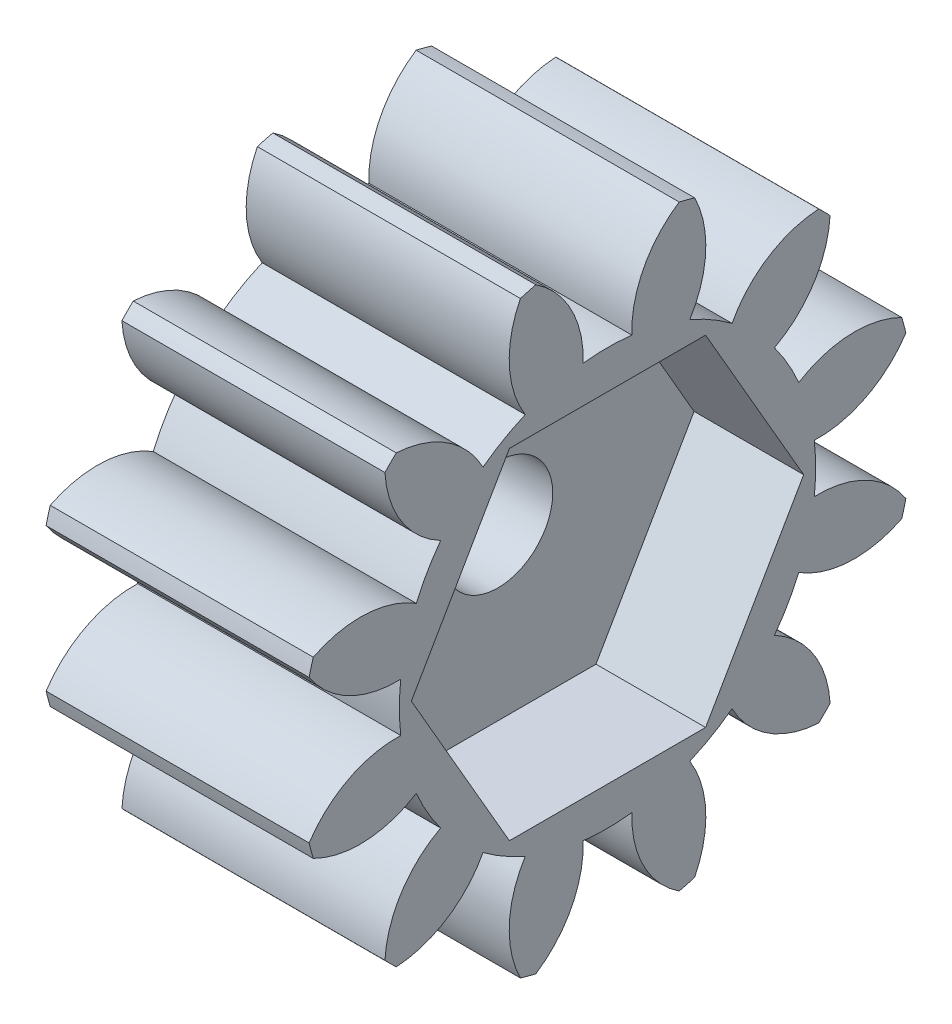
SolidWorks part; units mm, degrees
ref_plane "Plane1" through (0, 0, 0) normal (0, 0, 1) x (1, 0, 0)
ref_plane "Plane2" through (0, 0, 0) normal (0, 1, 0) x (1, 0, 0)
ref_plane "Plane3" through (0, 0, 0) normal (1, 0, 0) x (0, 0, -1)
sketch "HoldingSke" plane through (0, 0, 0) normal (0, 1, 0) x (1, 0, 0)
  line L0 (0, 0) -> (0.4891, -0.104)
  line L1 (-15, 0) -> (100, 0) construction
  line L2 (0, 0) -> (-2.1039, 2.3779)
  line L3 (0, 0) -> (-11.863, 4.5341)
  line L4 (0, 0) -> (8.4473, 1.7955)
  line L5 (0, 0) -> (-46.8476, -17.4728)
  line L6 (0, 0) -> (-9.9476, -6.7116)
  line L7 (-2.1039, 2.3779) -> (8.6586, 51.2059)
  line L8 (-76.2, 54.61) -> (-75.3, 54.61)
  line L9 (-71.009, 38.7566) -> (-53.1078, 45.2721)
  line L10 (-76.2, 71.12) -> (104.1128, 71.12)
  line L11 (0, 0) -> (-12, 0)
  line L12 (-76.2, 101.6) -> (-76.133, 101.6)
  line L13 (24.9733, 27.94) -> (52.9518, 28.4284)
  line L14 (24.9733, 27.94) -> (24.9743, 27.94)
  line L15 (24.9733, 27.94) -> (100.4006, 29.5858)
  line L16 (-63.627, -2) -> (-12.827, -2)
  circle A0 centre (0, 0) radius 2.5
  circle A1 centre (0, 0) radius 9.499
  circle A2 centre (0, 0) radius 37.5
  circle A3 centre (0, 0) radius 2.5
  dimension "MHD" = 18.998
  dimension "Hub_dia" = 75
  dimension "Bore" = 5
  dimension "MBD" = 5
  dimension "Num_teeth" = 12
  dimension "Pitch_radius" = 180.3128
  dimension "Pitch" = 0.5
  dimension "Width" = 12
  dimension "Overall_len" = 50
  dimension "Show_teeth" = 12
  dimension "Thickness" = 12
  dimension "OAL" = 50.0001
  dimension "T_dim" = 0.9
  dimension "Ap" = 20
  dimension "H" = 19.05
  dimension "Backlash" = 0.067
  dimension "Addendum_fac" = 1
  dimension "Dedendum_fac" = 1.25
  dimension "Clearance_fac" = 0.25
  dimension "Dedendum_add" = 0.001
  dimension "Module" = 2
sketch "BasProSke" plane through (0, 0, 0) normal (0, 1, 0) x (1, 0, 0)
  line L0 (-10, 0) -> (60, 0) construction
  line L1 (0, 0) -> (0, 14)
  line L2 (0, 0) -> (12, 0)
  line L3 (12, 0) -> (12, 14)
  line L4 (12, 14) -> (0, 14)
  dimension "Diameter" = 28
  dimension "Thickness" = 12
revolve "Base-Revolve" add sketch "BasProSke" angle 360 about L0
sketch "TooCutSke" plane through (0, 0, 0) normal (1, 0, 0) x (0, 0, -1)
  line L1 (0, 0) -> (0, 107) construction
  line L2 (0, 0) -> (-1.6834, 11.8813) construction
  line L3 (0, 0) -> (-6.1662, 23.0126) construction
  line L4 (-1.6834, 11.8813) -> (-3.0831, 11.5063) construction
  arc A0 (1.1119, 9.4337) -> (-1.1119, 9.4337) centre (0, 0) ccw
  arc A1 (3.2981, 13.6321) -> (-3.2981, 13.6321) centre (0, 0) ccw
  circle A2 centre (0, 0) radius 12 construction
  circle A3 centre (0, 0) radius 11.2763 construction
  arc A4 (-1.1119, 9.4337) -> (-3.2981, 13.6321) centre (-5.9089, 9.6042) ccw
  arc A5 (3.2981, 13.6321) -> (1.1119, 9.4337) centre (5.9089, 9.6042) ccw
  dimension "Root_dia" = 18.998
  dimension "Overcut_dia" = 28.0508
  dimension "Pitch_dia" = 24
  dimension "Base_dia" = 22.5526
  dimension "Flank_rad" = 4.8
  dimension "Half_ang" = 15
  dimension "Half_CT" = 1.4491
extrude "ToothCut" cut sketch "TooCutSke" along normal through all
fillet "Breaks" [suppressed] radius 0.04
fillet "RootFillets" [suppressed] radius 0.501
pattern_circular "TeethCuts" count 12 every 30 about axis through (-10, 0, 0) along (1, 0, 0) of "ToothCut", "RootFillets", "Breaks"
sketch "HubNeaOneSke" [suppressed] plane through (0, 0, 0) normal (-1, 0, 0) x (0, 0, 1)
  circle A0 centre (0, 0) radius 12.7
  dimension "Diameter" = 18.998
extrude "HubNearOne" [suppressed] add sketch "HubNeaOneSke" along normal blind 38.0001
sketch "HubNeaBotSke" [suppressed] plane through (0, 0, 0) normal (-1, 0, 0) x (0, 0, 1)
  circle A0 centre (0, 0) radius 12.7
  dimension "Diameter" = 18.998
extrude "HubNearBoth" [suppressed] add sketch "HubNeaBotSke" along normal blind 19
ref_plane "FarPln" through (12, 0, 0) normal (1, 0, 0) x (0, 0, -1)
sketch "HubFarSke" [suppressed] plane through (12.7, 0, 0) normal (1, 0, 0) x (0, 0, -1)
  circle A0 centre (0, 0) radius 12.7
  dimension "Diameter" = 18.998
extrude "HubFar" [suppressed] add sketch "HubFarSke" along normal blind 19
sketch "BorSke" plane through (0, 0, 0) normal (1, 0, 0) x (0, 0, -1)
  circle A0 centre (0, 0) radius 2.5
  dimension "Diameter" = 5
extrude "Bore" cut sketch "BorSke" along normal mid plane 100.0001
sketch "KeySke" [suppressed] plane through (0, 0, 0) normal (1, 0, 0) x (0, 0, -1)
  line L0 (-3.175, 0) -> (-3.175, 12.065)
  line L1 (-3.175, 12.065) -> (3.175, 12.065)
  line L2 (3.175, 12.065) -> (3.175, 0)
  line L3 (0, 0) -> (0, 34) construction
  line L4 (-3.175, 0) -> (3.175, 0)
  dimension "Offset" = 3.4
  dimension "Width" = 2
extrude "Keyway" [suppressed] cut sketch "KeySke" along normal mid plane 100.0001
pattern_circular "Keyway2" [suppressed] count 2 every 90 about axis through (-10, 0, 0) along (1, 0, 0)
sketch "Эскиз1" plane through (12, 0, 0) normal (1, 0, 0) x (0, 0, -1)
  line L1 (8.9489, 0) -> (4.4745, 7.75)
  line L2 (4.4745, 7.75) -> (-4.4745, 7.75)
  line L3 (-4.4745, 7.75) -> (-8.9489, 0)
  line L4 (-8.9489, 0) -> (-4.4745, -7.75)
  line L5 (-4.4745, -7.75) -> (4.4745, -7.75)
  line L6 (4.4745, -7.75) -> (8.9489, 0)
  circle A0 centre (0, 0) radius 7.75 construction
extrude "Вырез-Вытянуть1" cut sketch "Эскиз1" against normal blind 5
equation "' \"Module@HoldingSke\" = 6.35"
equation "' \"Num_teeth@HoldingSke\" = 12"
equation "' \"Ap@HoldingSke\" =  20"
equation "' \"Width@HoldingSke\" = 0.5 * 25.4"
equation "' \"Hub_dia@HoldingSke\"= 1 * 25.4"
equation "' \"Overall_len@HoldingSke\" = 1.0 * 25.4"
equation "' \"Bore@HoldingSke\" = 0.75 * 25.4"
equation "' \"T_dim@HoldingSke\" = 0.1 * 25.4"
equation "' \"Width@KeySke\" = 0.25 * 25.4"
equation "' \"Show_teeth@HoldingSke\" = 13"
equation "' \"Backlash@HoldingSke\" = 0.009 * 25.4"
equation "' \"Addendum_fac@HoldingSke\" = 1.0"
equation "' \"Dedendum_fac@HoldingSke\" = 1.25"
equation "' \"Dedendum_add@HoldingSke\" = 0.00005 * 25.4"
equation "' \"Clearance_fac@HoldingSke\" = 0.25"
equation "\"Pitch@HoldingSke\" = 1 / \"Module@HoldingSke\""
equation "\"Overcut_dia@TooCutSke\" = (\"Num_teeth@HoldingSke\" + 2 * \"Addendum_fac@HoldingSke\") / \"Pitch@HoldingSke\" + 0.002 * 25.4"
equation "\"Pitch_dia@TooCutSke\" = \"Num_teeth@HoldingSke\" / \"Pitch@HoldingSke\""
equation "\"Base_dia@TooCutSke\" = \"Num_teeth@HoldingSke\" / \"Pitch@HoldingSke\" * cos((\"Ap@HoldingSke\"  * 3.14159265 / 180))"
equation "\"Root_dia@TooCutSke\" = (\"Num_teeth@HoldingSke\" + 2) / \"Pitch@HoldingSke\" - 2 * (\"Addendum_fac@HoldingSke\" + \"Dedendum_fac@HoldingSke\") / \"Pitch@HoldingSke\" - \"Dedendum_add@HoldingSke\" * 2"
equation "\"Half_ang@TooCutSke\" = 180 / \"Num_teeth@HoldingSke\""
equation "\"Half_CT@TooCutSke\" = \"Num_teeth@HoldingSke\" / \"Pitch@HoldingSke\" * sin((3.14159265 / 2 / \"Num_teeth@HoldingSke\")) / 2 - 7 * \"Backlash@HoldingSke\" / 4"
equation "\"Flank_rad@TooCutSke\" = \"Num_teeth@HoldingSke\" / \"Pitch@HoldingSke\" / 5"
equation "\"Radius@RootFillets\" = \"Clearance_fac@HoldingSke\" / \"Pitch@HoldingSke\" + \"Dedendum_add@HoldingSke\""
equation "\"Break_rad@Breaks\" = 0.02 / \"Pitch@HoldingSke\""
equation "\"Thickness@HoldingSke\" = \"Width@HoldingSke\""
equation "\"OAL@HoldingSke\" = \"Thickness@HoldingSke\""
equation "\"MHD@HoldingSke\" = (\"Num_teeth@HoldingSke\" + 2) / \"Pitch@HoldingSke\" - 2 * (\"Addendum_fac@HoldingSke\" + \"Dedendum_fac@HoldingSke\")  / \"Pitch@HoldingSke\" - \"Dedendum_add@HoldingSke\" * 2"
equation "\"MBD@HoldingSke\" = (\"Num_teeth@HoldingSke\" + 2) / \"Pitch@HoldingSke\" - 2 * (\"Addendum_fac@HoldingSke\" + \"Dedendum_fac@HoldingSke\")  / \"Pitch@HoldingSke\" - \"Dedendum_add@HoldingSke\" * 2 - 0.002 * 25.4"
equation "\"MHD@HoldingSke\" = ((sgn( \"MHD@HoldingSke\" - \"Hub_dia@HoldingSke\" )-1)*( \"MHD@HoldingSke\" - \"Hub_dia@HoldingSke\" ))/-2+ \"Hub_dia@HoldingSke\""
equation "\"MBD@HoldingSke\" = ((sgn( \"MBD@HoldingSke\" - \"Bore@HoldingSke\" )-1)*( \"MBD@HoldingSke\" - \"Bore@HoldingSke\" ))/-2+ \"Bore@HoldingSke\""
equation "\"OAL@HoldingSke\" = ((sgn( \"OAL@HoldingSke\" - \"Overall_len@HoldingSke\" )+1)*( \"OAL@HoldingSke\" - \"Overall_len@HoldingSke\" ))/2 + \"Overall_len@HoldingSke\" + 0.000002 * 25.4"
equation "\"Num_teeth@TeethCuts\" = int( \"Show_teeth@HoldingSke\" ) + 1"
equation "\"Num_teeth@TeethCuts\" = ((sgn( \"Num_teeth@TeethCuts\" - \"Num_teeth@HoldingSke\" )-1)*( \"Num_teeth@TeethCuts\" - \"Num_teeth@HoldingSke\" ))/-2+ \"Num_teeth@HoldingSke\""
equation "\"Num_teeth@TeethCuts\" = ((sgn( \"Num_teeth@TeethCuts\" - 2.0)+1)*( \"Num_teeth@TeethCuts\" - 2.0))/2 +2.0"
equation "\"Angle@TeethCuts\" = 360.0 / \"Num_teeth@HoldingSke\""
equation "\"Diameter@BasProSke\" = (\"Num_teeth@HoldingSke\" + 2 * \"Addendum_fac@HoldingSke\") / \"Pitch@HoldingSke\""
equation "\"Thickness@BasProSke\"  = \"Thickness@HoldingSke\""
equation "' \"Fillet_rad@BasProSke\" =  \"Thickness@HoldingSke\" * 0.05"
equation "\"MHD@HoldingSke\" = ((sgn( \"MHD@HoldingSke\" - \"Root_dia@TooCutSke\" )-1)*( \"MHD@HoldingSke\" - \"Root_dia@TooCutSke\" ))/-2+ \"Root_dia@TooCutSke\""
equation "\"Diameter@HubNeaOneSke\" = \"MHD@HoldingSke\""
equation "\"Length@HubNearOne\" = \"OAL@HoldingSke\" - \"Thickness@BasProSke\""
equation "\"Diameter@HubNeaBotSke\" = \"MHD@HoldingSke\""
equation "\"Length@HubNearBoth\" = ( \"OAL@HoldingSke\" - \"Thickness@BasProSke\" ) / 2.0"
equation "\"Thickness@FarPln\" = \"Thickness@BasProSke\""
equation "\"Diameter@HubFarSke\" = \"MHD@HoldingSke\""
equation "\"Length@HubFar\" = ( \"OAL@HoldingSke\" - \"Thickness@BasProSke\" ) / 2.0"
equation "\"Diameter@BorSke\" = \"MBD@HoldingSke\""
equation "\"D1@Bore\" = \"OAL@HoldingSke\" * 2.0"
equation "\"D1@Keyway\" = \"OAL@HoldingSke\" * 2.0"
equation "\"Offset@KeySke\" = \"T_dim@HoldingSke\" + \"MBD@HoldingSke\" / 2.0"
